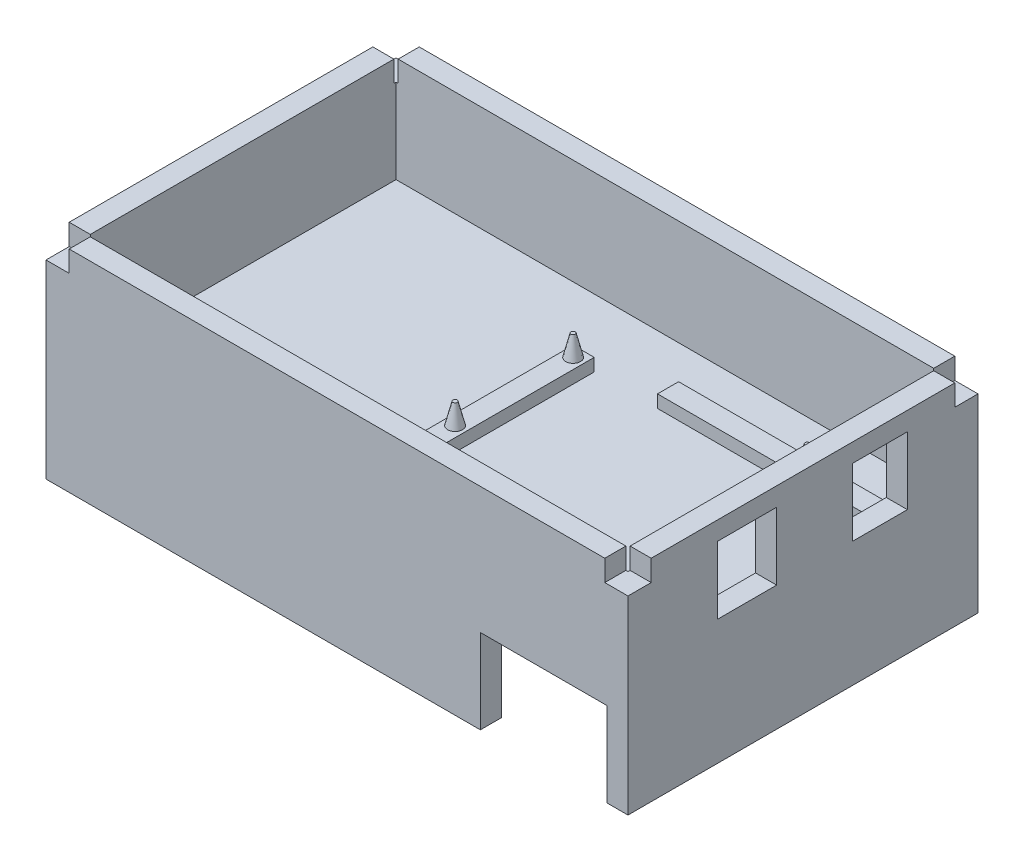
SolidWorks part; units mm, degrees
ref_plane "Ebene vorne" through (0, 0, 0) normal (0, 0, 1) x (1, 0, 0)
ref_plane "Ebene oben" through (0, 0, 0) normal (0, 1, 0) x (1, 0, 0)
ref_plane "Ebene rechts" through (0, 0, 0) normal (1, 0, 0) x (0, 0, -1)
sketch "Sketch1" plane through (0, 0, 0) normal (0, 1, 0) x (1, 0, 0)
  line L1 (-69, -41.5) -> (69, -41.5)
  line L2 (-69, -41.5) -> (-69, 41.5)
  line L3 (-69, 41.5) -> (69, 41.5)
  line L4 (69, -41.5) -> (69, 41.5)
  line L5 (-69, -41.5) -> (69, 41.5) construction
  line L6 (-69, 41.5) -> (69, -41.5) construction
  point P0 (0, 0)
  dimension "D1" = 138
  dimension "D2" = 83
extrude "Boss-Extrude1" add sketch "Sketch1" along normal blind 5
sketch "Sketch2" plane through (0, 0, 0) normal (0, -1, 0) x (1, 0, 0)
  line L1 (-69, -41.5) -> (69, -41.5)
  line L2 (-69, -41.5) -> (-69, 41.5)
  line L3 (-69, 41.5) -> (69, 41.5)
  line L4 (69, -41.5) -> (69, 41.5)
  line L5 (-69, -41.5) -> (69, 41.5) construction
  line L6 (-69, 41.5) -> (69, -41.5) construction
  line L7 (-64, -36.5) -> (64, -36.5)
  line L8 (-64, -36.5) -> (-64, 36.5)
  line L9 (-64, 36.5) -> (64, 36.5)
  line L10 (64, -36.5) -> (64, 36.5)
  line L11 (-64, -36.5) -> (64, 36.5) construction
  line L12 (-64, 36.5) -> (64, -36.5) construction
  point P0 (0, 0)
  point P5 (0, 0)
  dimension "D1" = 128
  dimension "D2" = 73
extrude "Boss-Extrude2" add sketch "Sketch2" along normal blind 20
sketch "Sketch3" plane through (0, 0, 36.5) normal (0, 0, -1) x (-1, 0, 0)
  line L0 (-64, -20) -> (64, -20) construction
  line L1 (-64, 0) -> (-34, 0)
  line L2 (-64, 0) -> (-64, -20)
  line L3 (-64, -20) -> (-34, -20)
  line L4 (-34, 0) -> (-34, -20)
  dimension "D1" = 30
extrude "Cut-Extrude1" cut sketch "Sketch3" against normal up to next
sketch "Sketch4" plane through (0, 5, 0) normal (0, 1, 0) x (1, 0, 0)
  line L0 (34, -36.5) -> (-64, -36.5) construction
  line L1 (69, 41.5) -> (-69, 41.5)
  line L2 (69, 41.5) -> (69, -41.5)
  line L3 (69, -41.5) -> (-69, -41.5)
  line L4 (-69, 41.5) -> (-69, -41.5)
  line L5 (69, 41.5) -> (-69, -41.5) construction
  line L6 (69, -41.5) -> (-69, 41.5) construction
  line L7 (64, 36.5) -> (-64, 36.5)
  line L8 (64, 36.5) -> (64, -36.5)
  line L9 (64, -36.5) -> (-64, -36.5)
  line L10 (-64, 36.5) -> (-64, -36.5)
  line L11 (64, 36.5) -> (-64, -36.5) construction
  line L12 (64, -36.5) -> (-64, 36.5) construction
  line L13 (64, 36.5) -> (64, -41.5) construction
  point P0 (0, 0)
  point P5 (0, 0)
  dimension "D1" = 0
  dimension "D2" = 0
extrude "Boss-Extrude3" add sketch "Sketch4" along normal blind 25
sketch "Sketch5" plane through (0, 5, 0) normal (0, 1, 0) x (1, 0, 0)
  line L0 (64, -28.5) -> (14, -28.5)
  line L1 (64, -28.5) -> (64, -23.5)
  line L2 (14, -28.5) -> (14, -23.5)
  line L3 (64, -23.5) -> (14, -23.5)
  line L5 (64, -36.5) -> (64, 36.5) construction
  line L6 (64, 20.5) -> (14, 20.5)
  line L7 (64, 20.5) -> (64, 25.5)
  line L8 (14, 20.5) -> (14, 25.5)
  line L9 (64, 25.5) -> (14, 25.5)
  line L10 (-1, 20.5) -> (-1, -14.5)
  line L11 (-1, 20.5) -> (-6, 20.5)
  line L12 (-1, -14.5) -> (-6, -14.5)
  line L13 (-6, 20.5) -> (-6, -14.5)
  line L14 (64, 36.5) -> (-64, 36.5) construction
  line L15 (64, 36.5) -> (-64, 36.5) construction
  dimension "D1" = 44
  dimension "D2" = 5
  dimension "D3" = 5
  dimension "D4" = 5
  dimension "D5" = 50
  dimension "D6" = 0
  dimension "D7" = 35
  dimension "D8" = 65
  dimension "D9" = 16
  dimension "D10" = 11
extrude "Boss-Extrude10" add sketch "Sketch5" along normal blind 3
sketch "Sketch6" plane through (0, 8, 0) normal (0, 1, 0) x (1, 0, 0)
  line L0 (64, 23) -> (14, 23) construction
  line L1 (64, 20.5) -> (64, 25.5) construction
  line L2 (14, 25.5) -> (14, 20.5) construction
  line L4 (-3.5, -14.5) -> (-3.5, 20.5) construction
  line L5 (-6, -14.5) -> (-1, -14.5) construction
  line L6 (-1, 20.5) -> (-6, 20.5) construction
  line L7 (64, -26) -> (14, -26) construction
  line L8 (64, -28.5) -> (64, -23.5) construction
  line L9 (14, -23.5) -> (14, -28.5) construction
  line L10 (64, -23.5) -> (64, 20.5) construction
  circle A0 centre (47, 23) radius 1.75
  circle A1 centre (47, -26) radius 1.75
  circle A2 centre (-3.5, 18) radius 1.75
  circle A3 centre (-3.5, -10) radius 1.75
  dimension "D1" = 17
  dimension "D2" = 3.5
  dimension "D3" = 0
  dimension "D4" = 3.5
  dimension "D5" = 67.5
  dimension "D6" = 3.5
  dimension "D9" = 28
  dimension "D10" = 3.5
  dimension "D8" = 5
  dimension "D11" = 49
  dimension "D12" = 50.5
extrude "Boss-Extrude11" add sketch "Sketch6" along normal blind 5 draft 14
sketch "Sketch7" plane through (64, 0, 0) normal (-1, 0, 0) x (0, 0, 1)
  line L0 (-24.75, 9.6) -> (-24.75, 25.6)
  line L1 (-24.75, 9.6) -> (-11.75, 9.6)
  line L2 (-24.75, 25.6) -> (-11.75, 25.6)
  line L3 (-11.75, 9.6) -> (-11.75, 25.6)
  line L7 (23.5, 5) -> (-20.5, 5) construction
  dimension "D1" = 0
  dimension "D2" = 13
  dimension "D3" = 4.6
  dimension "D4" = 16
extrude "Cut-Extrude2" cut sketch "Sketch7" against normal up to next
sketch "Sketch8" plane through (64, 0, 0) normal (-1, 0, 0) x (0, 0, 1)
  line L0 (6.25, 9.6) -> (20.25, 9.6)
  line L1 (6.25, 9.6) -> (6.25, 25.6)
  line L2 (20.25, 9.6) -> (20.25, 25.6)
  line L3 (6.25, 25.6) -> (20.25, 25.6)
  line L4 (-24.75, 9.6) -> (-11.75, 9.6) construction
  line L5 (-11.75, 25.6) -> (-24.75, 25.6) construction
  point P4 (6.25, 17.6)
  dimension "D1" = 31
  dimension "D2" = 0
  dimension "D3" = 14
  dimension "D4" = 0
  dimension "D5" = 16
  dimension "D6" = 16
extrude "Cut-Extrude3" cut sketch "Sketch8" against normal up to next
sketch "Sketch11" plane through (0, 30, 0) normal (0, 1, 0) x (1, 0, 0)
  line L0 (-63.5, 36) -> (-63.5, 41.5)
  line L1 (-63.5, 36) -> (-69, 36)
  line L2 (-63.5, 41.5) -> (-69, 41.5)
  line L3 (-69, 36) -> (-69, 41.5)
  line L4 (69, 41.5) -> (-69, 41.5) construction
  line L5 (-63.5, -36) -> (-63.5, -41.5)
  line L6 (-63.5, -36) -> (-69, -36)
  line L7 (-63.5, -41.5) -> (-69, -41.5)
  line L8 (-69, -36) -> (-69, -41.5)
  line L9 (-69, -41.5) -> (69, -41.5) construction
  line L10 (63.5, -36) -> (63.5, -41.5)
  line L11 (63.5, -36) -> (69, -36)
  line L12 (63.5, -41.5) -> (69, -41.5)
  line L13 (69, -36) -> (69, -41.5)
  line L14 (63.5, 36) -> (63.5, 41.5)
  line L15 (63.5, 36) -> (69, 36)
  line L16 (63.5, 41.5) -> (69, 41.5)
  line L17 (69, 36) -> (69, 41.5)
  line L18 (-69, 41.5) -> (-69, -41.5) construction
  line L19 (69, -41.5) -> (69, 41.5) construction
  dimension "D1" = 0
  dimension "D2" = 0
  dimension "D3" = 0
  dimension "D4" = 0
  dimension "D5" = 5.5
  dimension "D6" = 5.5
  dimension "D7" = 5.5
  dimension "D8" = 5.5
  dimension "D9" = 5.5
  dimension "D10" = 5.5
  dimension "D11" = 5.5
  dimension "D12" = 5.5
extrude "Cut-Extrude7" cut sketch "Sketch11" against normal blind 5
